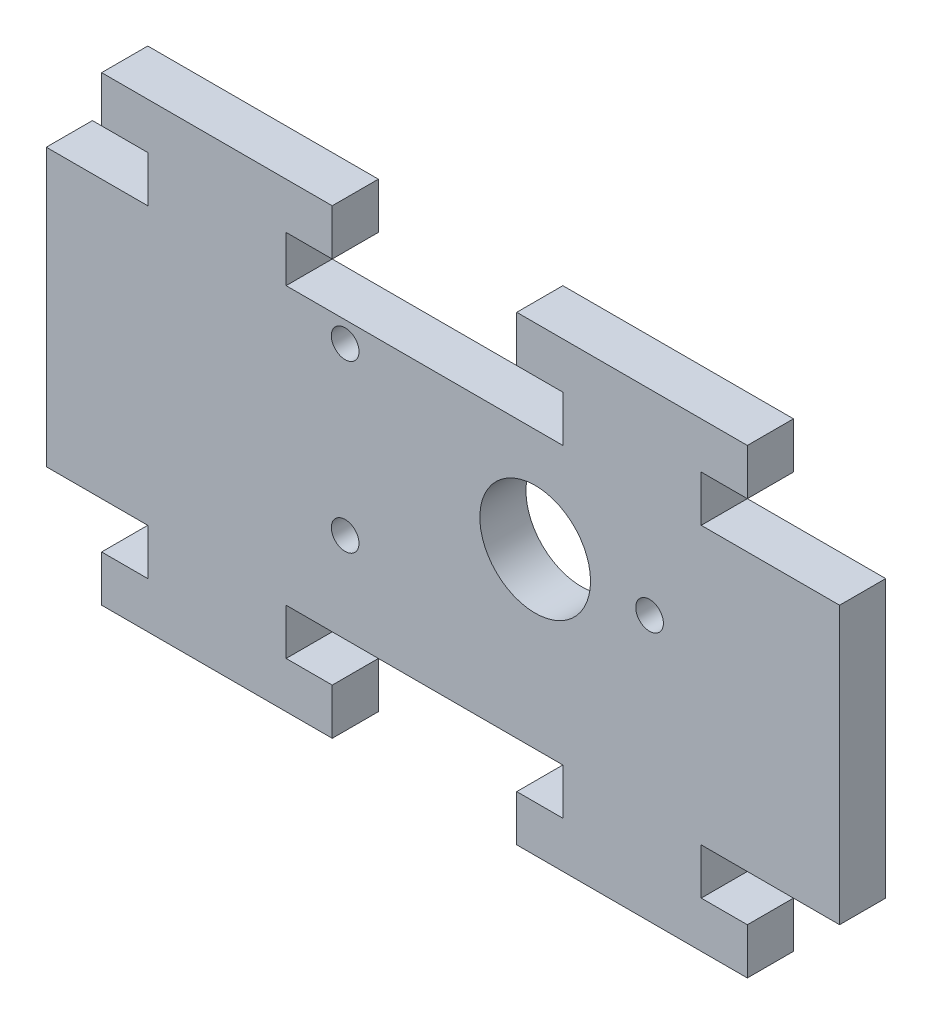
SolidWorks part; units mm, degrees
ref_plane "Front Plane" through (0, 0, 0) normal (0, 0, 1) x (1, 0, 0)
ref_plane "Top Plane" through (0, 0, 0) normal (0, 1, 0) x (1, 0, 0)
ref_plane "Right Plane" through (0, 0, 0) normal (1, 0, 0) x (0, 0, -1)
sketch "Sketch1" plane through (0, 0, 0) normal (0, 0, 1) x (1, 0, 0)
  line L0 (11, 27.5) -> (6, 27.5)
  line L1 (0, 22.5) -> (11, 22.5)
  line L2 (0, 22.5) -> (0, -7.5)
  line L3 (0, -7.5) -> (11, -7.5)
  line L4 (86, 22.5) -> (86, -7.5)
  line L6 (11, -7.5) -> (11, -12.5)
  line L7 (11, -17.5) -> (26, -17.5)
  line L8 (26, -7.5) -> (26, -12.5)
  line L10 (56, -7.5) -> (56, -12.5)
  line L11 (56, -17.5) -> (71, -17.5)
  line L12 (71, -7.5) -> (71, -12.5)
  line L14 (11, 22.5) -> (11, 27.5)
  line L16 (26, 22.5) -> (26, 27.5)
  line L18 (56, 22.5) -> (56, 27.5)
  line L19 (56, 32.5) -> (71, 32.5)
  line L20 (71, 22.5) -> (71, 27.5)
  line L21 (6, 27.5) -> (6, 32.5)
  line L22 (6, 32.5) -> (31, 32.5)
  line L23 (31, 32.5) -> (31, 27.5)
  line L24 (31, 27.5) -> (26, 27.5)
  line L26 (26, 22.5) -> (56, 22.5)
  line L27 (56, 27.5) -> (51, 27.5)
  line L28 (51, 27.5) -> (51, 32.5)
  line L29 (51, 32.5) -> (56, 32.5)
  line L30 (71, 27.5) -> (76, 27.5)
  line L31 (76, 27.5) -> (76, 32.5)
  line L32 (76, 32.5) -> (71, 32.5)
  line L33 (11, -17.5) -> (6, -17.5)
  line L34 (6, -17.5) -> (6, -12.5)
  line L35 (6, -12.5) -> (11, -12.5)
  line L36 (26, -17.5) -> (31, -17.5)
  line L37 (31, -17.5) -> (31, -12.5)
  line L38 (31, -12.5) -> (26, -12.5)
  line L39 (56, -17.5) -> (51, -17.5)
  line L40 (51, -17.5) -> (51, -12.5)
  line L41 (51, -12.5) -> (56, -12.5)
  line L42 (71, -17.5) -> (76, -17.5)
  line L43 (76, -17.5) -> (76, -12.5)
  line L44 (76, -12.5) -> (71, -12.5)
  line L45 (71, -7.5) -> (86, -7.5)
  line L46 (71, 22.5) -> (86, 22.5)
  line L47 (26, -7.5) -> (56, -7.5)
  circle A0 centre (32.4, 20.25) radius 1.5
  circle A1 centre (32.4, 2.25) radius 1.5
  circle A2 centre (53, 11.25) radius 6
  circle A3 centre (65.4, 11.25) radius 1.5
  dimension "D1" = 12
  dimension "D2" = 3
  dimension "D3" = 3
  dimension "D4" = 10
  dimension "D5" = 10
  dimension "D6" = 5
  dimension "D7" = 10
  dimension "D8" = 5
  dimension "D9" = 5
extrude "Boss-Extrude1" add sketch "Sketch1" along normal blind 5
